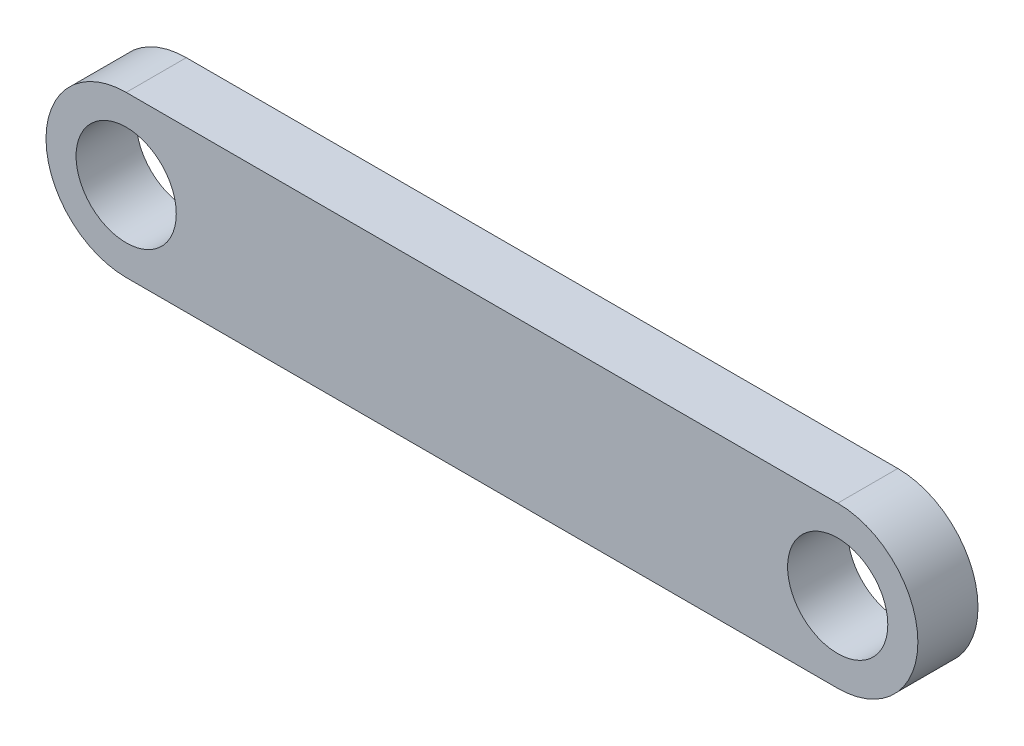
SolidWorks part; units mm, degrees
material "ABS"
ref_plane "Front Plane" through (0, 0, 0) normal (0, 0, 1) x (1, 0, 0)
ref_plane "Top Plane" through (0, 0, 0) normal (0, 1, 0) x (1, 0, 0)
ref_plane "Right Plane" through (0, 0, 0) normal (1, 0, 0) x (0, 0, -1)
sketch "Sketch1" plane through (0, 0, 0) normal (0, 0, 1) x (1, 0, 0)
  line L0 (0, 0) -> (-35.5, 0)
  dimension "D1" = 35.5
sketch "Sketch2" plane through (0, 0, 0) normal (0, 0, 1) x (1, 0, 0)
  line L0 (-35.5, 4) -> (0, 4)
  line L1 (-35.5, -4) -> (0, -4)
  circle A0 centre (-35.5, 0) radius 2.5
  circle A1 centre (0, 0) radius 2.5
  arc A2 (-35.5, 4) -> (-35.5, -4) centre (-35.5, 0) ccw
  arc A3 (0, -4) -> (0, 4) centre (0, 0) ccw
  dimension "D1" = 5
  dimension "D2" = 8
  dimension "D3" = 5
  dimension "D4" = 8
extrude "Boss-Extrude1" add sketch "Sketch2" along normal blind 3
